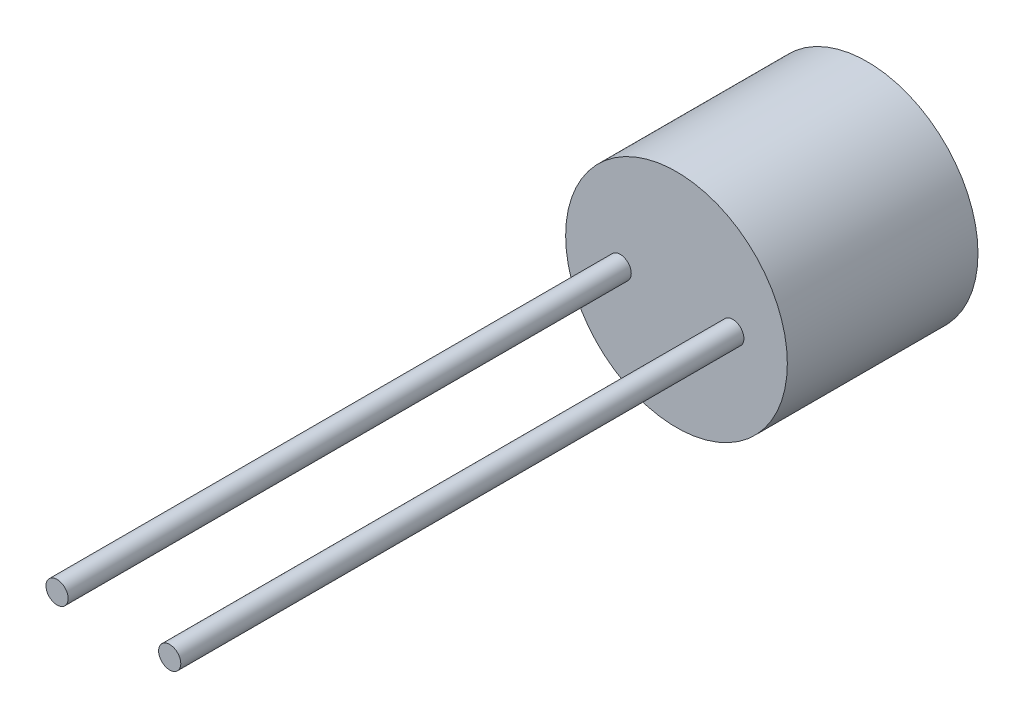
SolidWorks part; units mm, degrees
ref_plane "前视基准面" through (0, 0, 0) normal (0, 0, 1) x (1, 0, 0)
ref_plane "上视基准面" through (0, 0, 0) normal (0, 1, 0) x (1, 0, 0)
ref_plane "右视基准面" through (0, 0, 0) normal (1, 0, 0) x (0, 0, -1)
sketch "草图1" plane through (0, 0, 0) normal (0, 0, 1) x (1, 0, 0)
  circle A0 centre (0, 0) radius 2.5
  dimension "D1" = 5
extrude "拉伸1" add sketch "草图1" along normal blind 3.3
sketch "草图2" plane through (0, 0, 3.3) normal (0, 0, 1) x (1, 0, 0)
  circle A0 centre (0, 0) radius 2.5
  dimension "D1" = 5
extrude "拉伸2" add sketch "草图2" along normal blind 1
sketch "草图3" plane through (0, 0, 4.3) normal (0, 0, 1) x (1, 0, 0)
  line L0 (0, 2.011) -> (0, -2.1052) construction
  line L1 (-2.1813, 0) -> (2.3335, 0) construction
  circle A0 centre (-1.27, 0) radius 0.25
  circle A1 centre (1.27, 0) radius 0.25
  dimension "D1" = 0.5
  dimension "D2" = 2.54
extrude "拉伸3" add sketch "草图3" along normal blind 12.7
sketch "草图4" plane through (0, 0, 4.3) normal (0, 0, 1) x (1, 0, 0)
  point P0 (0, 0)
